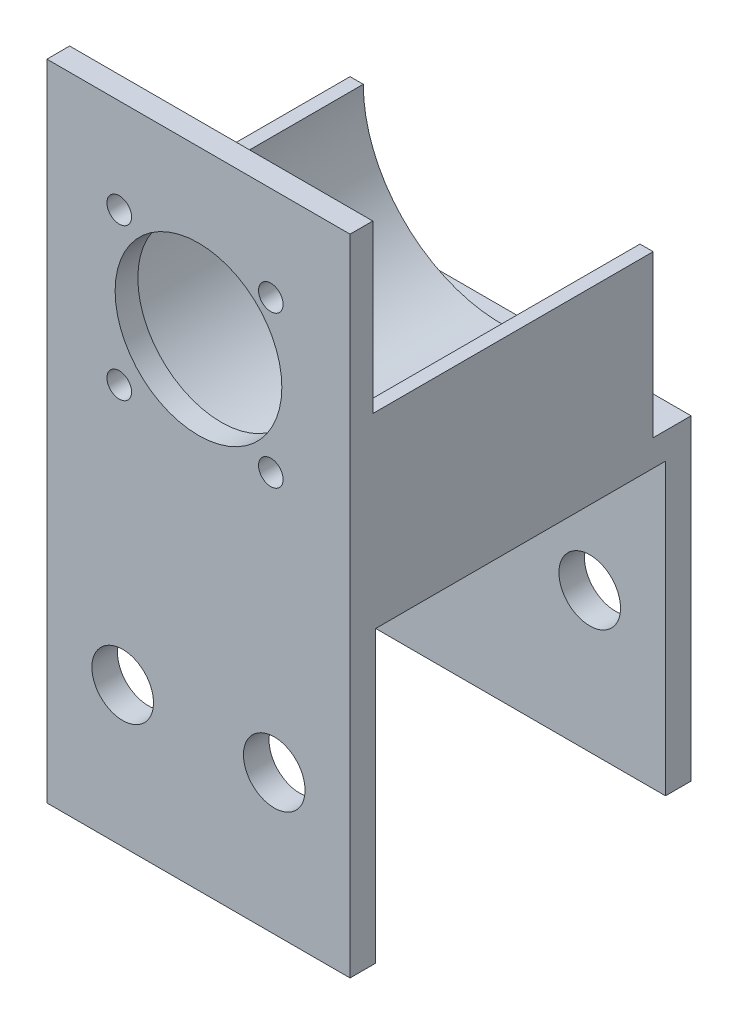
SolidWorks part; units mm, degrees
ref_plane "Plan de face" through (0, 0, 0) normal (0, 0, 1) x (1, 0, 0)
ref_plane "Plan de dessus" through (0, 0, 0) normal (0, 1, 0) x (1, 0, 0)
ref_plane "Plan de droite" through (0, 0, 0) normal (1, 0, 0) x (0, 0, -1)
sketch "Esquisse1" plane through (0, 0, 0) normal (0, 0, 1) x (1, 0, 0)
  line L1 (0, 0) -> (40, 0)
  line L2 (0, 0) -> (0, 85)
  line L3 (0, 85) -> (40, 85)
  line L4 (40, 0) -> (40, 85)
  dimension "D1" = 85
  dimension "D2" = 40
extrude "Boss.-Extru.1" add sketch "Esquisse1" along normal blind 45
sketch "Esquisse2" plane through (40, 0, 0) normal (1, 0, 0) x (0, 0, -1)
  line L0 (-45, 0) -> (0, 0) construction
  line L1 (-41.625, 0) -> (-3.375, 0)
  line L2 (-41.625, 0) -> (-41.625, 38.25)
  line L3 (-41.625, 38.25) -> (-3.375, 38.25)
  line L4 (-3.375, 0) -> (-3.375, 38.25)
  dimension "D1" = 38.25
  dimension "D2" = 38.25
  dimension "D3" = 3.375
  dimension "D4" = 3.375
extrude "Enlèv. mat.-Extru.1" cut sketch "Esquisse2" against normal blind 41.1
sketch "Esquisse3" plane through (0, 0, 45) normal (1, 0, 0) x (0, 0, -1)
  line L0 (0, 85) -> (45, 85) construction
  line L1 (45, 85) -> (3, 85)
  line L2 (45, 85) -> (45, 63)
  line L3 (45, 63) -> (3, 63)
  line L4 (3, 85) -> (3, 63)
  line L6 (45, 85) -> (45, 0) construction
  dimension "D1" = 3
  dimension "D2" = 22
extrude "Enlèv. mat.-Extru.2" cut sketch "Esquisse3" along normal through all
sketch "Esquisse4" plane through (0, 0, 0) normal (0, 0, 1) x (1, 0, 0)
  line L2 (40, 63) -> (0, 63) construction
  circle A0 centre (20, 63) radius 18.2562
  dimension "D1" = 36.5125
extrude "Enlèv. mat.-Extru.3" cut sketch "Esquisse4" along normal up to surface (42 mm away) up to face at (20, 74, 42)
sketch "Esquisse5" plane through (37, 0, 0) normal (0, 0, -1) x (-1, 0, 0)
  circle A0 centre (17, 63) radius 11
  dimension "D1" = 22
extrude "Enlèv. mat.-Extru.4" cut sketch "Esquisse5" against normal through all and the other way through all
sketch "Esquisse6" plane through (0, 0, 42) normal (0, 0, -1) x (-1, 0, 0)
  line L0 (-20, 63) -> (-29.5459, 72.5459)
  line L2 (-28.9838, 63) -> (-20, 63)
  circle A2 centre (-29.5459, 72.5459) radius 1.625
  circle A3 centre (-29.5459, 52.5459) radius 1.625
  circle A4 centre (-9.5459, 52.5459) radius 1.625
  circle A5 centre (-9.5459, 72.5459) radius 1.625
  circle A7 centre (-20, 63) radius 11 construction
  point P9 (-20, 63)
  point P17 (-27.7782, 70.7782)
  dimension "D1" = 20
  dimension "D2" = 3.25
  dimension "D5" = 2.5
  dimension "D3" = 45
  dimension "D4" = 20
extrude "Enlèv. mat.-Extru.5" cut sketch "Esquisse6" against normal through all contours A2 | A3 | A5 | A4
sketch "Esquisse7" plane through (0, 0, 41.625) normal (0, 0, -1) x (-1, 0, 0)
  line L0 (-40, 0) -> (-40, 63) construction
  line L1 (0, 63) -> (0, 0) construction
  line L2 (0, 38.25) -> (-40, 38.25) construction
  line L3 (0, 0) -> (-40, 0) construction
  circle A0 centre (-10, 18.4875) radius 4.065
  circle A1 centre (-30, 18.4875) radius 4.065
  dimension "D1" = 8.13
  dimension "D2" = 20
  dimension "D3" = 10
  dimension "D4" = 10
  dimension "D5" = 19.7625
  dimension "D6" = 18.4875
extrude "Enlèv. mat.-Extru.6" cut sketch "Esquisse7" against normal through all both and the other way through all
sketch "Esquisse8" plane through (0, 0, 0) normal (-1, 0, 0) x (0, 0, 1)
  line L1 (0, 63) -> (5, 63)
  line L2 (0, 63) -> (0, 41.7437)
  line L3 (0, 41.7437) -> (5, 41.7437)
  line L4 (5, 63) -> (5, 41.7437)
  dimension "D1" = 3
  dimension "D2" = 5
extrude "Enlèv. mat.-Extru.7" cut sketch "Esquisse8" against normal through all
